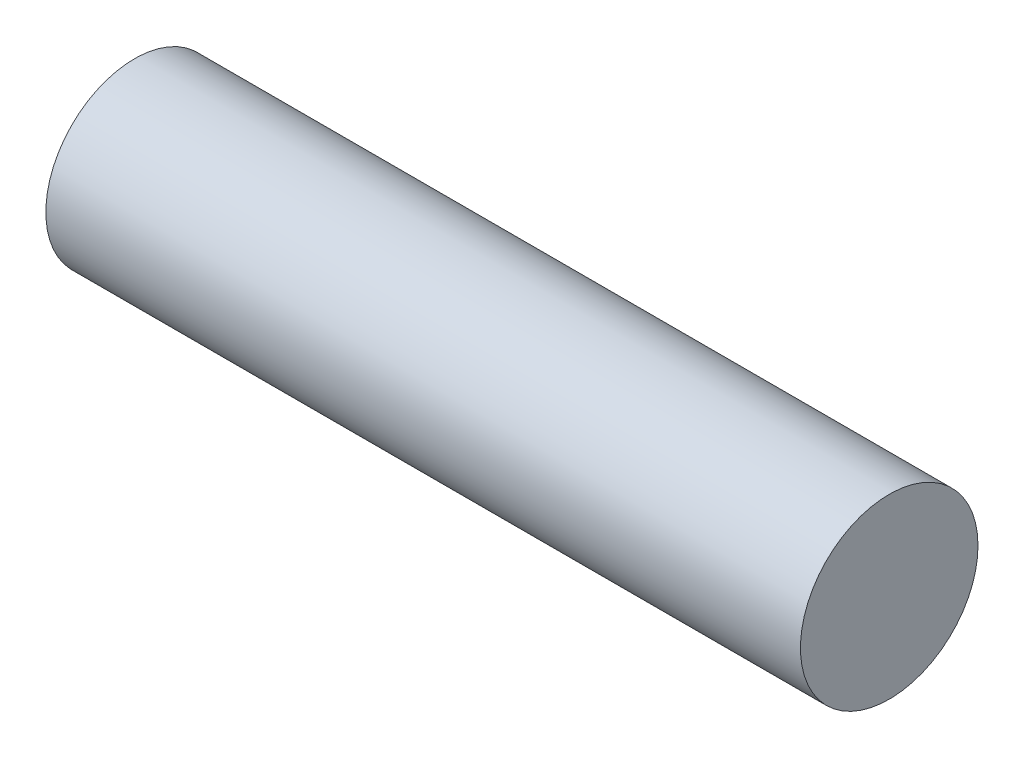
SolidWorks part; units mm, degrees
material "Stainless Steel (ferritic)"
ref_plane "Front Plane" through (0, 0, 0) normal (0, 0, 1) x (1, 0, 0)
ref_plane "Top Plane" through (0, 0, 0) normal (0, 1, 0) x (1, 0, 0)
ref_plane "Right Plane" through (0, 0, 0) normal (1, 0, 0) x (0, 0, -1)
sketch "Sketch1" plane through (0, 0, 0) normal (1, 0, 0) x (0, 0, -1)
  circle A0 centre (0, 0) radius 2
  dimension "D1" = 4
extrude "Boss-Extrude1" add sketch "Sketch1" along normal blind 17
